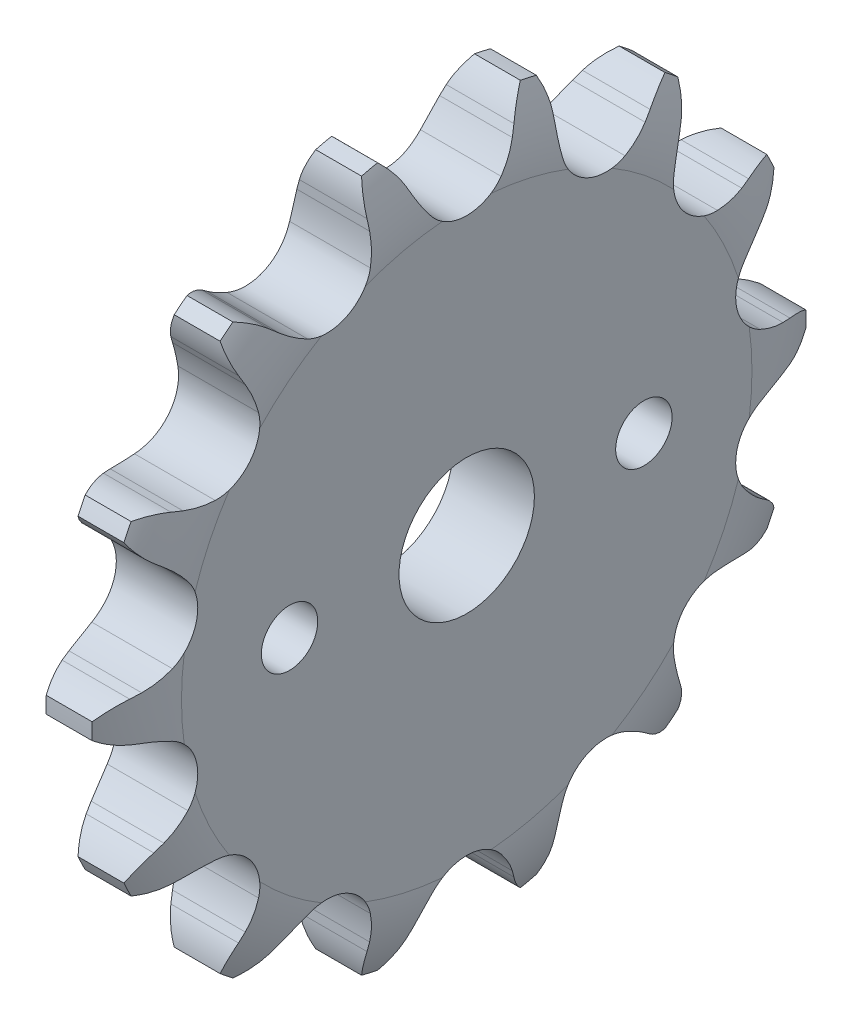
SolidWorks part; units mm, degrees
material "AISI 4340 Steel, normalized"
ref_plane "Plane1" through (0, 0, 0) normal (0, 0, 1) x (1, 0, 0)
ref_plane "Plane2" through (0, 0, 0) normal (0, 1, 0) x (1, 0, 0)
ref_plane "Plane3" through (0, 0, 0) normal (1, 0, 0) x (0, 0, -1)
sketch "Clipboard" plane through (0, 0, 0) normal (0, 1, 0) x (1, 0, 0)
  line L0 (0, 0) -> (12.3228, -3.0724)
  line L1 (-15, 0) -> (100, 0) construction
  line L2 (0, 0) -> (-1.0435, 1.1794)
  line L3 (0, 0) -> (-5.9315, 2.2671)
  line L4 (0, 0) -> (7.6894, 1.9172)
  line L5 (0, 0) -> (-47.5972, -17.7524)
  line L6 (0, 0) -> (-5.9832, -4.0369)
  line L7 (-1.0435, 1.1794) -> (48.0255, 14.3274)
  line L8 (-76.2, 38.1) -> (-73.5584, 38.1)
  line L9 (-73.2057, 38.5609) -> (-73.0533, 38.5634)
  line L10 (-73.0533, 76.1892) -> (-58.6769, 76.1892)
  circle A0 centre (0, 0) radius 3.9624
  circle A1 centre (0, 0) radius 21.4562
  circle A2 centre (0, 0) radius 38.1
  dimension "Dr" = 7.9248
  dimension "MHD" = 42.9123
  dimension "Hub_dia" = 76.2
  dimension "Num_teeth" = 14
  dimension "Pitch" = 12.7
  dimension "Width" = 7.9248
  dimension "Chamfer_wid" = 1.5748
  dimension "Chamfer_dep" = 6.35
  dimension "Overall_len" = 50.8
  dimension "Show_teeth" = 14
  dimension "Thickness" = 7.2177
  dimension "OAL" = 50.8
  dimension "T_dim" = 2.6416
  dimension "Width_const" = 0.1524
  dimension "Width_factor" = 0.93
  dimension "Num_strands" = 1
  dimension "Transv_pitch" = 14.3764
sketch "BasProSke" plane through (0, 0, 0) normal (0, 1, 0) x (1, 0, 0)
  line L0 (-10, 0) -> (60, 0) construction
  line L1 (0, 0) -> (0, 25.2812)
  line L2 (0, 0) -> (7.2177, 0)
  line L3 (7.2177, 0) -> (7.2177, 25.2812)
  line L4 (5.6429, 31.6312) -> (1.5748, 31.6312)
  arc A0 (0, 25.2812) -> (1.5748, 31.6312) centre (13.5898, 25.2812) cw
  arc A1 (7.2177, 25.2812) -> (5.6429, 31.6312) centre (-6.3722, 25.2812) ccw
  dimension "Thickness" = 7.2177
  dimension "D1" = 13.5898
  dimension "G1" = 1.5748
  dimension "G2" = 1.5748
  dimension "H2" = 6.35
  dimension "H1" = 6.35
  dimension "Diameter" = 63.2623
revolve "Base-Revolve" add sketch "BasProSke" angle 360 about L0
sketch "GrvSke" plane through (0, 0, 0) normal (0, 1, 0) x (1, 0, 0)
  line L0 (7.2177, 25.2812) -> (7.2177, 21.4562)
  line L1 (7.2177, 21.4562) -> (14.3764, 21.4562)
  line L2 (14.3764, 21.4562) -> (14.3764, 25.2812)
  line L3 (5.6429, 31.6312) -> (15.9512, 31.6312)
  line L4 (10.797, 0) -> (10.797, 52.07) construction
  line L5 (-10, 0) -> (60, 0) construction
  line L6 (0, 0) -> (35.56, 0) construction
  arc A0 (14.3764, 25.2812) -> (15.9512, 31.6312) centre (27.9662, 25.2812) cw
  arc A1 (7.2177, 25.2812) -> (5.6429, 31.6312) centre (-6.3722, 25.2812) ccw
  dimension "G1" = 1.5748
  dimension "H1" = 6.35
  dimension "Diameter" = 63.2623
  dimension "Grv_diam" = 42.9123
  dimension "Grv_width" = 7.1587
  dimension "Offset" = 10.797
revolve "Groove" [suppressed] cut sketch "GrvSke" angle 360 about L6
pattern_linear "Grooves" [suppressed]
sketch "TooCutSke" plane through (0, 0, 0) normal (1, 0, 0) x (0, 0, -1)
  line L0 (4.4274, 28.1414) -> (4.7922, 28.9137)
  line L1 (0, 0) -> (0, 107) construction
  line L2 (0, 28.5366) -> (-10, 28.5366) construction
  line L3 (-4.4274, 28.1414) -> (-4.7922, 28.9137)
  arc A0 (3.0834, 26.0142) -> (4.4274, 28.1414) centre (-4.907, 32.551) ccw
  arc A1 (3.0834, 26.0142) -> (-3.0834, 26.0142) centre (0, 28.5366) cw
  arc A2 (4.7922, 28.9137) -> (10.8166, 32.7305) centre (10.8166, 26.0678) cw
  arc A3 (-3.0834, 26.0142) -> (-4.4274, 28.1414) centre (4.907, 32.551) cw
  arc A4 (-4.7922, 28.9137) -> (-10.8166, 32.7305) centre (-10.8166, 26.0678) ccw
  arc A5 (10.8166, 32.7305) -> (-10.8166, 32.7305) centre (0, 0) ccw
  dimension "R" = 3.9837
  dimension "E" = 10.3236
  dimension "F" = 6.6627
  dimension "Pitch_radius" = 28.5366
  dimension "W" = 10.8166
  dimension "V" = 2.4688
  dimension "A" = 39.286
  dimension "B" = 14
extrude "ToothCut" cut sketch "TooCutSke" along normal through all
pattern_circular "TeethCuts" count 14 every 25.714 about axis through (-10, 0, 0) along (1, 0, 0) of "ToothCut"
sketch "HubNeaOneSke" plane through (0, 0, 0) normal (-1, 0, 0) x (0, 0, 1)
  circle A0 centre (0, 0) radius 21.4562
  dimension "Diameter" = 42.9123
extrude "HubNearOne" [suppressed] add sketch "HubNeaOneSke" along normal blind 43.5823
sketch "HubNeaBotSke" plane through (0, 0, 0) normal (-1, 0, 0) x (0, 0, 1)
  circle A0 centre (0, 0) radius 21.4562
  dimension "Diameter" = 42.9123
extrude "HubNearBoth" [suppressed] add sketch "HubNeaBotSke" along normal blind 21.7912
ref_plane "FarPln" through (7.2177, 0, 0) normal (1, 0, 0) x (0, 0, -1)
sketch "HubFarSke" plane through (7.2177, 0, 0) normal (1, 0, 0) x (0, 0, -1)
  circle A0 centre (0, 0) radius 21.4562
  dimension "Diameter" = 42.9123
extrude "HubFar" [suppressed] add sketch "HubFarSke" along normal blind 21.7912
sketch "BorSke" plane through (0, 0, 0) normal (1, 0, 0) x (0, 0, -1)
  circle A0 centre (0, 0) radius 1.1913
  dimension "Diameter" = 2.3825
extrude "Bore" cut sketch "BorSke" along normal mid plane 101.6
sketch "KeySke" plane through (0, 0, 0) normal (1, 0, 0) x (0, 0, -1)
  line L0 (-0.127, 0) -> (-0.127, 1.4503)
  line L1 (-0.127, 1.4503) -> (0.127, 1.4503)
  line L2 (0.127, 1.4503) -> (0.127, 0)
  line L3 (0, 0) -> (0, 34) construction
  line L4 (-0.127, 0) -> (0.127, 0)
  dimension "Offset" = 1.4503
  dimension "Width" = 0.254
extrude "Keyway" [suppressed] cut sketch "KeySke" along normal mid plane 101.6
pattern_circular "Keyway2" [suppressed] count 2 every 90 about axis through (-10, 0, 0) along (1, 0, 0)
ref_plane "Plane4" through (0, 28.5216, 6.5099) normal (0, 0.9749, 0.2225) x (1, 0, 0)
sketch "Sketch2" plane through (7.2177, 0, 0) normal (1, 0, 0) x (0, 0, -1)
  line L0 (-15.7028, 0) -> (15.7028, 0)
  circle A0 centre (0, 0) radius 6
  circle A1 centre (-15.7028, 0) radius 2.5
  circle A2 centre (15.7028, 0) radius 2.5
  point P6 (0, 0)
  dimension "D1" = 5
  dimension "D2" = 5
  dimension "D3" = 12
extrude "Cut-Extrude1" cut sketch "Sketch2" against normal blind 10
equation "\"Num_teeth@Clipboard\" = int( \"Num_teeth@Clipboard\" )"
equation "\"Num_teeth@Clipboard\" = ((sgn( \"Num_teeth@Clipboard\" - 5.0)+1)*( \"Num_teeth@Clipboard\" - 5.0))/2 +5.0"
equation "\"Num_teeth@Clipboard\" = ((sgn( \"Num_teeth@Clipboard\" - 200.0)-1)*( \"Num_teeth@Clipboard\" - 200.0))/-2 +200.0"
equation "\"MHD@Clipboard\" = \"Pitch@Clipboard\" * (1.0 / tan(3.14159265 / \"Num_teeth@Clipboard\" ) - 1.0) - 0.03"
equation "\"Thickness@Clipboard\"  = \"Width@Clipboard\" * \"Width_factor@Clipboard\" - \"Width_const@Clipboard\" + (\"Num_strands@Clipboard\" - 1) * \"Transv_pitch@Clipboard\""
equation "\"OAL@Clipboard\" = \"Thickness@Clipboard\""
equation "\"MHD@Clipboard\" = ((sgn( \"MHD@Clipboard\" - \"Hub_dia@Clipboard\" )-1)*( \"MHD@Clipboard\" - \"Hub_dia@Clipboard\" ))/-2+ \"Hub_dia@Clipboard\""
equation "\"OAL@Clipboard\" = ((sgn( \"OAL@Clipboard\" - \"Overall_len@Clipboard\" )+1)*( \"OAL@Clipboard\" - \"Overall_len@Clipboard\" ))/2 + \"Overall_len@Clipboard\" + 0.000002"
equation "\"Num_teeth@TeethCuts\" = int( \"Show_teeth@Clipboard\" ) + 1"
equation "\"Num_teeth@TeethCuts\" = ((sgn( \"Num_teeth@TeethCuts\" - \"Num_teeth@Clipboard\" )-1)*( \"Num_teeth@TeethCuts\" - \"Num_teeth@Clipboard\" ))/-2+ \"Num_teeth@Clipboard\""
equation "\"Num_teeth@TeethCuts\" = ((sgn( \"Num_teeth@TeethCuts\" - 2.0)+1)*( \"Num_teeth@TeethCuts\" - 2.0))/2 +2.0"
equation "\"Angle@TeethCuts\" = 360.0 / \"Num_teeth@Clipboard\""
equation "\"Pitch_radius@TooCutSke\" = ( \"Pitch@Clipboard\" / 2.0) / sin(3.14159265 / \"Num_teeth@Clipboard\" )  'ma"
equation "\"R@TooCutSke\"  = \"Dr@Clipboard\" * 0.5025 + 0.0015"
equation "\"A@TooCutSke\" = 35.0 + (60.0 / \"Num_teeth@Clipboard\")"
equation "\"E@TooCutSke\"  = \"Dr@Clipboard\" * 1.3025 + 0.0015"
equation "\"B@TooCutSke\"  = 18.0 - (56.0 / \"Num_teeth@Clipboard\" )"
equation "\"W@TooCutSke\" = 1.4 * \"Dr@Clipboard\" * cos(3.14159265 / \"Num_teeth@Clipboard\" )"
equation "\"V@TooCutSke\" = 1.4 * \"Dr@Clipboard\" * sin(3.14159265 / \"Num_teeth@Clipboard\" )"
equation "\"Diameter@BasProSke\" = 2.0 * ( (0.3 * \"Pitch@Clipboard\" ) +  \"Pitch@Clipboard\" / 2.0 / tan(3.14159265 / \"Num_teeth@Clipboard\" ))"
equation "\"Thickness@BasProSke\"  = \"Thickness@Clipboard\""
equation "\"G1@BasProSke\" =  \"Chamfer_wid@Clipboard\""
equation "\"G2@BasProSke\" =  \"Chamfer_wid@Clipboard\""
equation "\"H1@BasProSke\" =  \"Chamfer_dep@Clipboard\""
equation "\"H2@BasProSke\" =  \"Chamfer_dep@Clipboard\""
equation "\"Diameter@GrvSke\" = \"Diameter@BasProSke\""
equation "\"G1@GrvSke\" = \"Chamfer_wid@Clipboard\""
equation "\"H1@GrvSke\" = \"Chamfer_dep@Clipboard\""
equation "\"Grv_diam@GrvSke\" =  \"Pitch@Clipboard\" * (1.0 / tan(3.14159265 / \"Num_teeth@Clipboard\" ) - 1.0) - 0.03"
equation "\"Grv_width@GrvSke\" =  \"Transv_pitch@Clipboard\" - ( \"Width@Clipboard\" * \"Width_factor@Clipboard\" - \"Width_const@Clipboard\" )"
equation "\"Offset@GrvSke\" = \"Grv_width@GrvSke\" / 2.0 + ( \"Width@Clipboard\" * \"Width_factor@Clipboard\" - \"Width_const@Clipboard\" )"
equation "\"Offset@Grooves\" = \"Transv_pitch@Clipboard\""
equation "\"Num_grvs@Grooves\" = \"Num_strands@Clipboard\""
equation "\"Num_grvs@Grooves\" = \"Num_grvs@Grooves\" - 1 * sgn( \"Num_grvs@Grooves\" -1)"
equation "\"Diameter@HubNeaOneSke\" = \"MHD@Clipboard\""
equation "\"Length@HubNearOne\" = \"OAL@Clipboard\" - \"Thickness@BasProSke\""
equation "\"Diameter@HubNeaBotSke\" = \"MHD@Clipboard\""
equation "\"Length@HubNearBoth\" = ( \"OAL@Clipboard\" - \"Thickness@BasProSke\" ) / 2.0"
equation "\"Thickness@FarPln\" = \"Thickness@BasProSke\""
equation "\"Diameter@HubFarSke\" = \"MHD@Clipboard\""
equation "\"Length@HubFar\" = ( \"OAL@Clipboard\" - \"Thickness@BasProSke\" ) / 2.0"
equation "\"D1@Bore\" = \"OAL@Clipboard\" * 2.0"
equation "\"D1@Keyway\" = \"OAL@Clipboard\" * 2.0"
equation "\"Offset@KeySke\" = \"T_dim@Clipboard\" - \"Diameter@BorSke\" / 2.0"
equation "\"D2@Sketch2\"=\"D1@Sketch2\""
